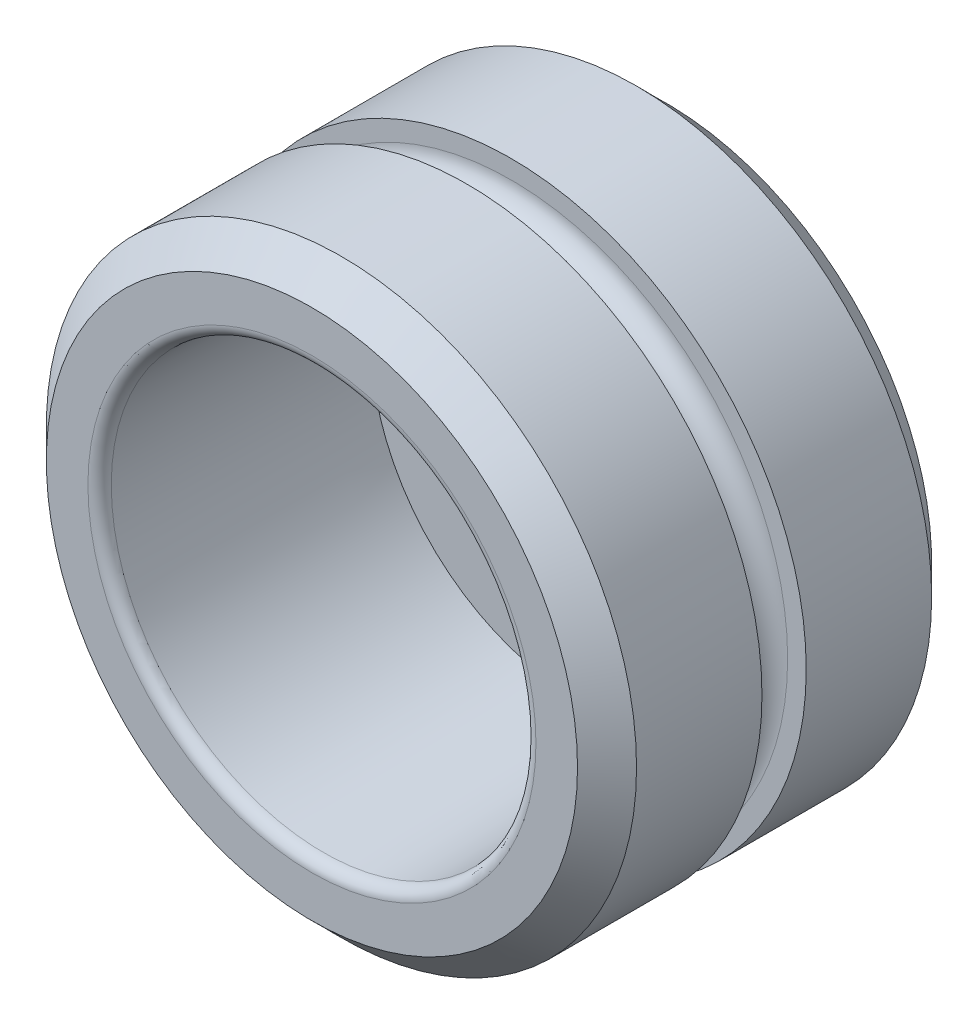
SolidWorks part; units mm, degrees
ref_plane "정면" through (0, 0, 0) normal (0, 0, 1) x (1, 0, 0)
ref_plane "윗면" through (0, 0, 0) normal (0, 1, 0) x (1, 0, 0)
ref_plane "우측면" through (0, 0, 0) normal (1, 0, 0) x (0, 0, -1)
sketch "스케치1" plane through (0, 0, 0) normal (0, 1, 0) x (1, 0, 0)
  line L0 (0, 0) -> (4, 0)
  line L1 (4, 0) -> (5.8947, 0.5)
  line L2 (5.8947, 0.5) -> (10, 0.5)
  line L3 (10, 0.5) -> (10, -4.75)
  line L4 (10, -11.5) -> (7.2, -11.5)
  line L5 (7.2, -11.5) -> (7, -2.5)
  line L6 (7, -2.5) -> (0, -2.5)
  line L7 (0, -2.5) -> (0, 0)
  line L8 (10, -4.75) -> (9.37, -4.75)
  line L9 (9.37, -6.25) -> (10, -6.25)
  line L10 (10, -6.25) -> (10, -11.5)
  arc A0 (9.37, -4.75) -> (9.37, -6.25) centre (9.37, -5.5) ccw
  dimension "D7" = 0.75
  dimension "D1" = 10
  dimension "D2" = 2.5
  dimension "D3" = 12
  dimension "D4" = 4
  dimension "D5" = 7
  dimension "D6" = 0.5
  dimension "D8" = 2.8
  dimension "D9" = 0.63
  dimension "D10" = 5.5
revolve "회전1" add sketch "스케치1" angle 360 about L7
chamfer "모따기1" distance 1 angle 45 2 edges at (10, 0, -0.5) (10, 0, 11.5)
fillet "필렛1" radius 0.4 2 edges at (5.8947, 0, -0.5) (7.2, 0, 11.5)
ref_plane "평면1" through (0, 0, 10) normal (0, 0, 1) x (1, 0, 0)
